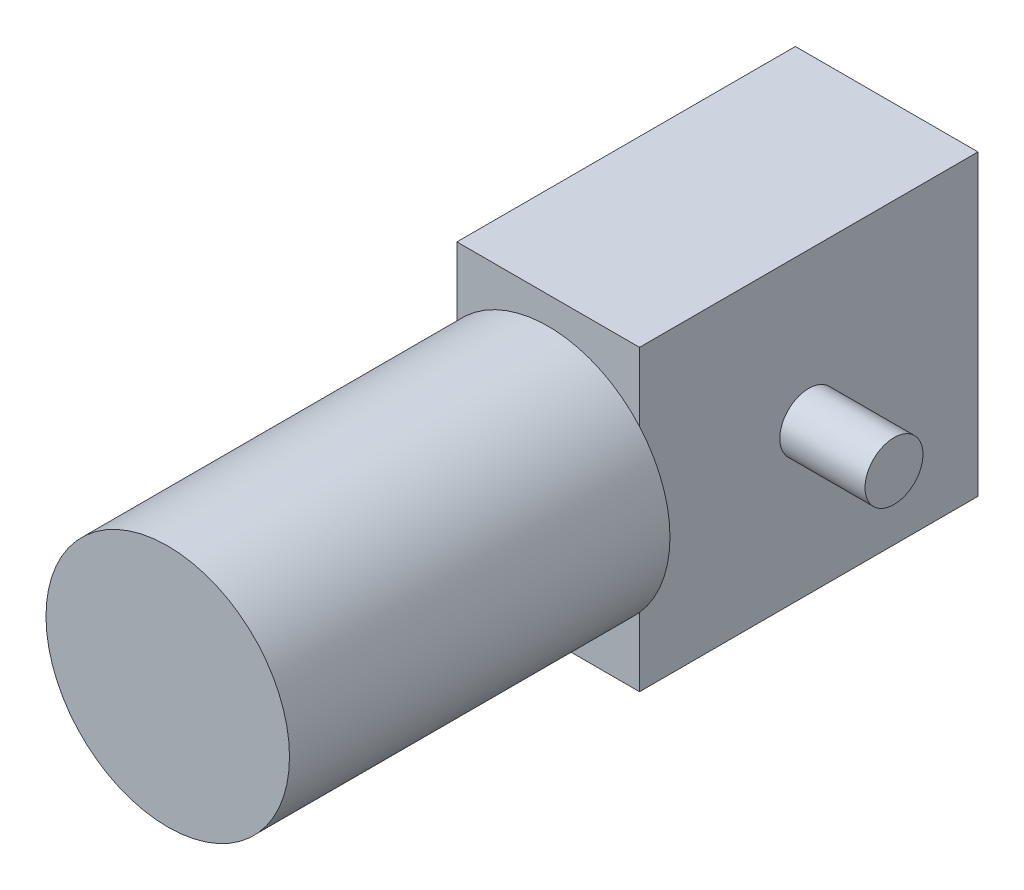
SolidWorks part; units mm, degrees
ref_plane "Alzado" through (0, 0, 0) normal (0, 0, 1) x (1, 0, 0)
ref_plane "Planta" through (0, 0, 0) normal (0, 1, 0) x (1, 0, 0)
ref_plane "Vista lateral" through (0, 0, 0) normal (1, 0, 0) x (0, 0, -1)
sketch "Croquis1" plane through (0, 0, 0) normal (0, 0, 1) x (1, 0, 0)
  line L1 (-60, -98) -> (60, -98)
  line L2 (-60, -98) -> (-60, 98)
  line L3 (-60, 98) -> (60, 98)
  line L4 (60, -98) -> (60, 98)
  line L5 (-60, -98) -> (60, 98) construction
  line L6 (-60, 98) -> (60, -98) construction
  point P0 (0, 0)
  dimension "D1" = 196
  dimension "D2" = 120
extrude "Saliente-Extruir1" add sketch "Croquis1" along normal mid plane 222.4
sketch "Croquis2" plane through (0, 0, 0) normal (1, 0, 0) x (0, 0, -1)
  circle A0 centre (0, 0) radius 19.05
  dimension "D1" = 38.1
extrude "Saliente-Extruir2" add sketch "Croquis2" along normal mid plane 232 separate body
sketch "Croquis3" plane through (0, 0, 111.2) normal (0, 0, 1) x (1, 0, 0)
  circle A0 centre (0, 0) radius 80
  dimension "D1" = 160
extrude "Saliente-Extruir3" add sketch "Croquis3" along normal blind 250
